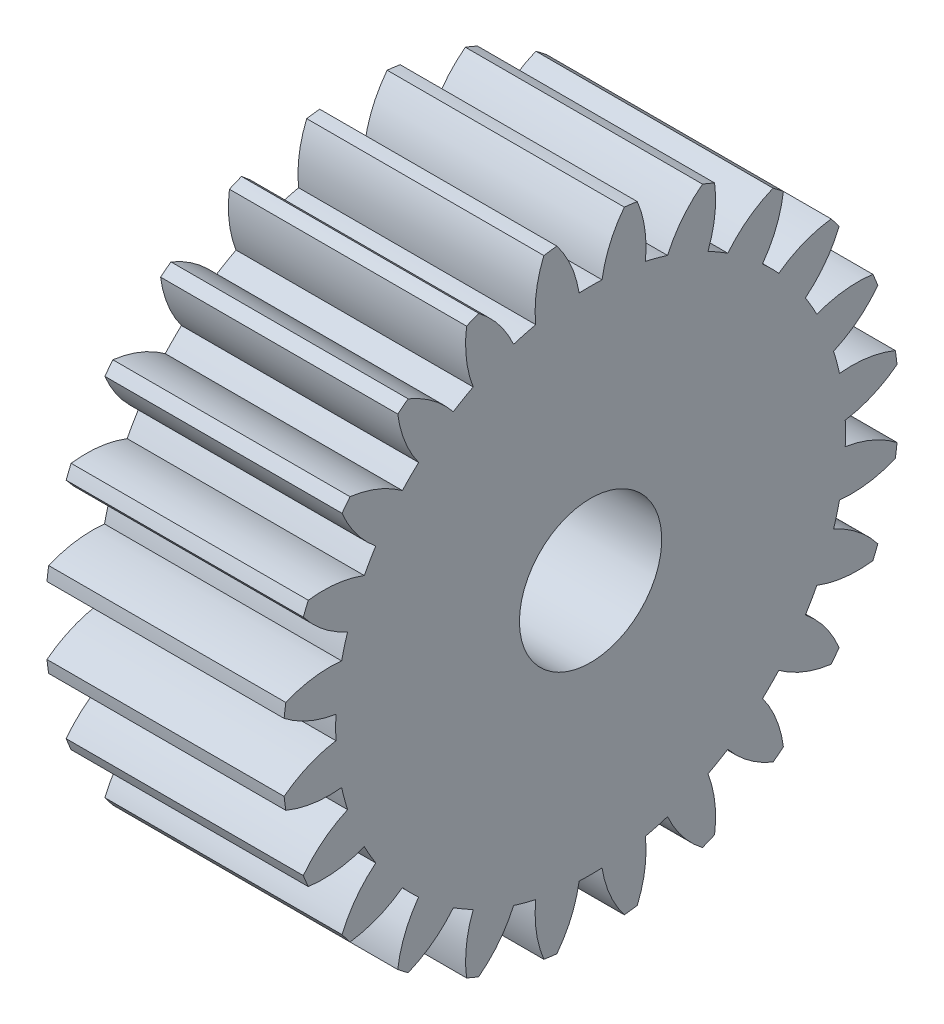
SolidWorks part; units mm, degrees
ref_plane "Plane1" through (0, 0, 0) normal (0, 0, 1) x (1, 0, 0)
ref_plane "Plane2" through (0, 0, 0) normal (0, 1, 0) x (1, 0, 0)
ref_plane "Plane3" through (0, 0, 0) normal (1, 0, 0) x (0, 0, -1)
sketch "HoldingSke" plane through (0, 0, 0) normal (0, 1, 0) x (1, 0, 0)
  line L0 (0, 0) -> (1.8271, -0.8135)
  line L1 (-15, 0) -> (100, 0) construction
  line L2 (0, 0) -> (-2.1039, 2.3779)
  line L3 (0, 0) -> (-11.863, 4.5341)
  line L4 (0, 0) -> (7.8894, 3.5126)
  line L5 (0, 0) -> (-46.8476, -17.4728)
  line L6 (0, 0) -> (-4.1448, -2.7965)
  line L7 (-2.1039, 2.3779) -> (8.6586, 51.2059)
  line L8 (-76.2, 54.61) -> (-75.7, 54.61)
  line L9 (-71.009, 38.7566) -> (-53.1078, 45.2721)
  line L10 (-76.2, 71.12) -> (104.1128, 71.12)
  line L11 (0, 0) -> (-5, 0)
  line L12 (-76.2, 101.6) -> (-76.181, 101.6)
  line L13 (24.9733, 27.94) -> (52.9518, 28.4284)
  line L14 (24.9733, 27.94) -> (24.9743, 27.94)
  line L15 (24.9733, 27.94) -> (100.4006, 29.5858)
  line L16 (-63.627, -0.5) -> (-12.827, -0.5)
  circle A0 centre (0, 0) radius 1.5
  circle A1 centre (0, 0) radius 5.374
  circle A2 centre (0, 0) radius 37.5
  circle A3 centre (0, 0) radius 1.5
  dimension "MHD" = 10.748
  dimension "Hub_dia" = 75
  dimension "Bore" = 3
  dimension "MBD" = 3
  dimension "Num_teeth" = 24
  dimension "Pitch" = 2
  dimension "Overall_len" = 50
  dimension "Show_teeth" = 24
  dimension "Thickness" = 5
  dimension "OAL" = 50.0001
  dimension "T_dim" = 0.5
  dimension "Ap" = 20
  dimension "H" = 19.05
  dimension "Pitch_radius" = 180.3128
  dimension "Width" = 5
  dimension "Backlash" = 0.019
  dimension "Addendum_fac" = 1
  dimension "Dedendum_fac" = 1.25
  dimension "Clearance_fac" = 0.25
  dimension "Dedendum_add" = 0.001
  dimension "Module" = 0.5
sketch "BasProSke" plane through (0, 0, 0) normal (0, 1, 0) x (1, 0, 0)
  line L0 (-10, 0) -> (60, 0) construction
  line L1 (0, 0) -> (0, 6.5)
  line L2 (0, 0) -> (5, 0)
  line L3 (5, 0) -> (5, 6.5)
  line L4 (5, 6.5) -> (0, 6.5)
  dimension "Thickness" = 5
  dimension "Diameter" = 13
revolve "Base-Revolve" add sketch "BasProSke" angle 360 about L0
sketch "TooCutSke" plane through (0, 0, 0) normal (1, 0, 0) x (0, 0, -1)
  line L1 (0, 0) -> (0, 107) construction
  line L2 (0, 0) -> (-0.4257, 5.9849) construction
  line L3 (0, 0) -> (-1.5635, 11.876) construction
  line L4 (-0.4257, 5.9849) -> (-0.7818, 5.938) construction
  arc A0 (0.2416, 5.3686) -> (-0.2416, 5.3686) centre (0, 0) ccw
  arc A1 (0.7297, 6.4845) -> (-0.7297, 6.4845) centre (0, 0) ccw
  circle A2 centre (0, 0) radius 6 construction
  circle A3 centre (0, 0) radius 5.6382 construction
  arc A4 (-0.2416, 5.3686) -> (-0.7297, 6.4845) centre (-2.6126, 4.9963) ccw
  arc A5 (0.7297, 6.4845) -> (0.2416, 5.3686) centre (2.6126, 4.9963) ccw
  dimension "Root_dia" = 10.748
  dimension "Overcut_dia" = 13.0508
  dimension "Pitch_dia" = 12
  dimension "Base_dia" = 11.2763
  dimension "Flank_rad" = 2.4
  dimension "Half_ang" = 7.5
  dimension "Half_CT" = 0.3592
extrude "ToothCut" cut sketch "TooCutSke" along normal through all
fillet "Breaks" [suppressed] radius 0.01
fillet "RootFillets" [suppressed] radius 0.126
pattern_circular "TeethCuts" count 24 every 15 about axis through (-10, 0, 0) along (1, 0, 0) of "ToothCut", "RootFillets", "Breaks"
sketch "HubNeaOneSke" plane through (0, 0, 0) normal (-1, 0, 0) x (0, 0, 1)
  circle A0 centre (0, 0) radius 5.374
  dimension "Diameter" = 10.748
extrude "HubNearOne" [suppressed] add sketch "HubNeaOneSke" along normal blind 45.0001
sketch "HubNeaBotSke" plane through (0, 0, 0) normal (-1, 0, 0) x (0, 0, 1)
  circle A0 centre (0, 0) radius 5.374
  dimension "Diameter" = 10.748
extrude "HubNearBoth" [suppressed] add sketch "HubNeaBotSke" along normal blind 22.5001
ref_plane "FarPln" through (5, 0, 0) normal (1, 0, 0) x (0, 0, -1)
sketch "HubFarSke" plane through (5, 0, 0) normal (1, 0, 0) x (0, 0, -1)
  circle A0 centre (0, 0) radius 5.374
  dimension "Diameter" = 10.748
extrude "HubFar" [suppressed] add sketch "HubFarSke" along normal blind 22.5001
sketch "BorSke" plane through (0, 0, 0) normal (1, 0, 0) x (0, 0, -1)
  circle A0 centre (0, 0) radius 1.5
  dimension "Diameter" = 3
extrude "Bore" cut sketch "BorSke" along normal mid plane 100.0002
sketch "KeySke" plane through (0, 0, 0) normal (1, 0, 0) x (0, 0, -1)
  line L0 (-0.6, 0) -> (-0.6, 2)
  line L1 (-0.6, 2) -> (0.6, 2)
  line L2 (0.6, 2) -> (0.6, 0)
  line L3 (0, 0) -> (0, 34) construction
  line L4 (-0.6, 0) -> (0.6, 0)
  dimension "Offset" = 2
  dimension "Width" = 1.2
extrude "Keyway" [suppressed] cut sketch "KeySke" along normal mid plane 100.0002
pattern_circular "Keyway2" [suppressed] count 2 every 90 about axis through (-10, 0, 0) along (1, 0, 0)
equation "' \"Module@HoldingSke\" = 6.35"
equation "' \"Num_teeth@HoldingSke\" = 12"
equation "' \"Ap@HoldingSke\" =  20"
equation "' \"Ap@HoldingSke\" = 20"
equation "' \"Width@HoldingSke\" = 0.5 * 25.4"
equation "' \"Hub_dia@HoldingSke\"= 1 * 25.4"
equation "' \"Hub_dia@HoldingSke\" = 1 * 25.4"
equation "' \"Overall_len@HoldingSke\" = 1.0 * 25.4"
equation "' \"Bore@HoldingSke\" = 0.75 * 25.4"
equation "' \"T_dim@HoldingSke\" = 0.1 * 25.4"
equation "' \"Width@KeySke\" = 0.25 * 25.4"
equation "' \"Show_teeth@HoldingSke\" = 13"
equation "' \"Backlash@HoldingSke\" = 0.009 * 25.4"
equation "' \"Addendum_fac@HoldingSke\" = 1.0"
equation "' \"Dedendum_fac@HoldingSke\" = 1.25"
equation "' \"Dedendum_add@HoldingSke\" = 0.00005 * 25.4"
equation "' \"Clearance_fac@HoldingSke\" = 0.25"
equation "\"Pitch@HoldingSke\" = 1 / \"Module@HoldingSke\""
equation "\"Overcut_dia@TooCutSke\" = (\"Num_teeth@HoldingSke\" + 2 * \"Addendum_fac@HoldingSke\") / \"Pitch@HoldingSke\" + 0.002 * 25.4"
equation "\"Pitch_dia@TooCutSke\" = \"Num_teeth@HoldingSke\" / \"Pitch@HoldingSke\""
equation "\"Base_dia@TooCutSke\" = \"Num_teeth@HoldingSke\" / \"Pitch@HoldingSke\" * cos((\"Ap@HoldingSke\"  * 3.14159265 / 180))"
equation "\"Root_dia@TooCutSke\" = (\"Num_teeth@HoldingSke\" + 2) / \"Pitch@HoldingSke\" - 2 * (\"Addendum_fac@HoldingSke\" + \"Dedendum_fac@HoldingSke\") / \"Pitch@HoldingSke\" - \"Dedendum_add@HoldingSke\" * 2"
equation "\"Half_ang@TooCutSke\" = 180 / \"Num_teeth@HoldingSke\""
equation "\"Half_CT@TooCutSke\" = \"Num_teeth@HoldingSke\" / \"Pitch@HoldingSke\" * sin((3.14159265 / 2 / \"Num_teeth@HoldingSke\")) / 2 - 7 * \"Backlash@HoldingSke\" / 4"
equation "\"Flank_rad@TooCutSke\" = \"Num_teeth@HoldingSke\" / \"Pitch@HoldingSke\" / 5"
equation "\"Radius@RootFillets\" = \"Clearance_fac@HoldingSke\" / \"Pitch@HoldingSke\" + \"Dedendum_add@HoldingSke\""
equation "\"Break_rad@Breaks\" = 0.02 / \"Pitch@HoldingSke\""
equation "\"Thickness@HoldingSke\" = \"Width@HoldingSke\""
equation "\"OAL@HoldingSke\" = \"Thickness@HoldingSke\""
equation "\"MHD@HoldingSke\" = (\"Num_teeth@HoldingSke\" + 2) / \"Pitch@HoldingSke\" - 2 * (\"Addendum_fac@HoldingSke\" + \"Dedendum_fac@HoldingSke\")  / \"Pitch@HoldingSke\" - \"Dedendum_add@HoldingSke\" * 2"
equation "\"MBD@HoldingSke\" = (\"Num_teeth@HoldingSke\" + 2) / \"Pitch@HoldingSke\" - 2 * (\"Addendum_fac@HoldingSke\" + \"Dedendum_fac@HoldingSke\")  / \"Pitch@HoldingSke\" - \"Dedendum_add@HoldingSke\" * 2 - 0.002 * 25.4"
equation "\"MHD@HoldingSke\" = ((sgn( \"MHD@HoldingSke\" - \"Hub_dia@HoldingSke\" )-1)*( \"MHD@HoldingSke\" - \"Hub_dia@HoldingSke\" ))/-2+ \"Hub_dia@HoldingSke\""
equation "\"MBD@HoldingSke\" = ((sgn( \"MBD@HoldingSke\" - \"Bore@HoldingSke\" )-1)*( \"MBD@HoldingSke\" - \"Bore@HoldingSke\" ))/-2+ \"Bore@HoldingSke\""
equation "\"OAL@HoldingSke\" = ((sgn( \"OAL@HoldingSke\" - \"Overall_len@HoldingSke\" )+1)*( \"OAL@HoldingSke\" - \"Overall_len@HoldingSke\" ))/2 + \"Overall_len@HoldingSke\" + 0.000002 * 25.4"
equation "\"Num_teeth@TeethCuts\" = int( \"Show_teeth@HoldingSke\" ) + 1"
equation "\"Num_teeth@TeethCuts\" = ((sgn( \"Num_teeth@TeethCuts\" - \"Num_teeth@HoldingSke\" )-1)*( \"Num_teeth@TeethCuts\" - \"Num_teeth@HoldingSke\" ))/-2+ \"Num_teeth@HoldingSke\""
equation "\"Num_teeth@TeethCuts\" = ((sgn( \"Num_teeth@TeethCuts\" - 2.0)+1)*( \"Num_teeth@TeethCuts\" - 2.0))/2 +2.0"
equation "\"Angle@TeethCuts\" = 360.0 / \"Num_teeth@HoldingSke\""
equation "\"Diameter@BasProSke\" = (\"Num_teeth@HoldingSke\" + 2 * \"Addendum_fac@HoldingSke\") / \"Pitch@HoldingSke\""
equation "\"Thickness@BasProSke\"  = \"Thickness@HoldingSke\""
equation "' \"Fillet_rad@BasProSke\" =  \"Thickness@HoldingSke\" * 0.05"
equation "' \"Fillet_rad@BasProSke\" = \"Thickness@HoldingSke\" * 0.05"
equation "\"MHD@HoldingSke\" = ((sgn( \"MHD@HoldingSke\" - \"Root_dia@TooCutSke\" )-1)*( \"MHD@HoldingSke\" - \"Root_dia@TooCutSke\" ))/-2+ \"Root_dia@TooCutSke\""
equation "\"Diameter@HubNeaOneSke\" = \"MHD@HoldingSke\""
equation "\"Length@HubNearOne\" = \"OAL@HoldingSke\" - \"Thickness@BasProSke\""
equation "\"Diameter@HubNeaBotSke\" = \"MHD@HoldingSke\""
equation "\"Length@HubNearBoth\" = ( \"OAL@HoldingSke\" - \"Thickness@BasProSke\" ) / 2.0"
equation "\"Thickness@FarPln\" = \"Thickness@BasProSke\""
equation "\"Diameter@HubFarSke\" = \"MHD@HoldingSke\""
equation "\"Length@HubFar\" = ( \"OAL@HoldingSke\" - \"Thickness@BasProSke\" ) / 2.0"
equation "\"Diameter@BorSke\" = \"MBD@HoldingSke\""
equation "\"D1@Bore\" = \"OAL@HoldingSke\" * 2.0"
equation "\"D1@Keyway\" = \"OAL@HoldingSke\" * 2.0"
equation "\"Offset@KeySke\" = \"T_dim@HoldingSke\" + \"MBD@HoldingSke\" / 2.0"
